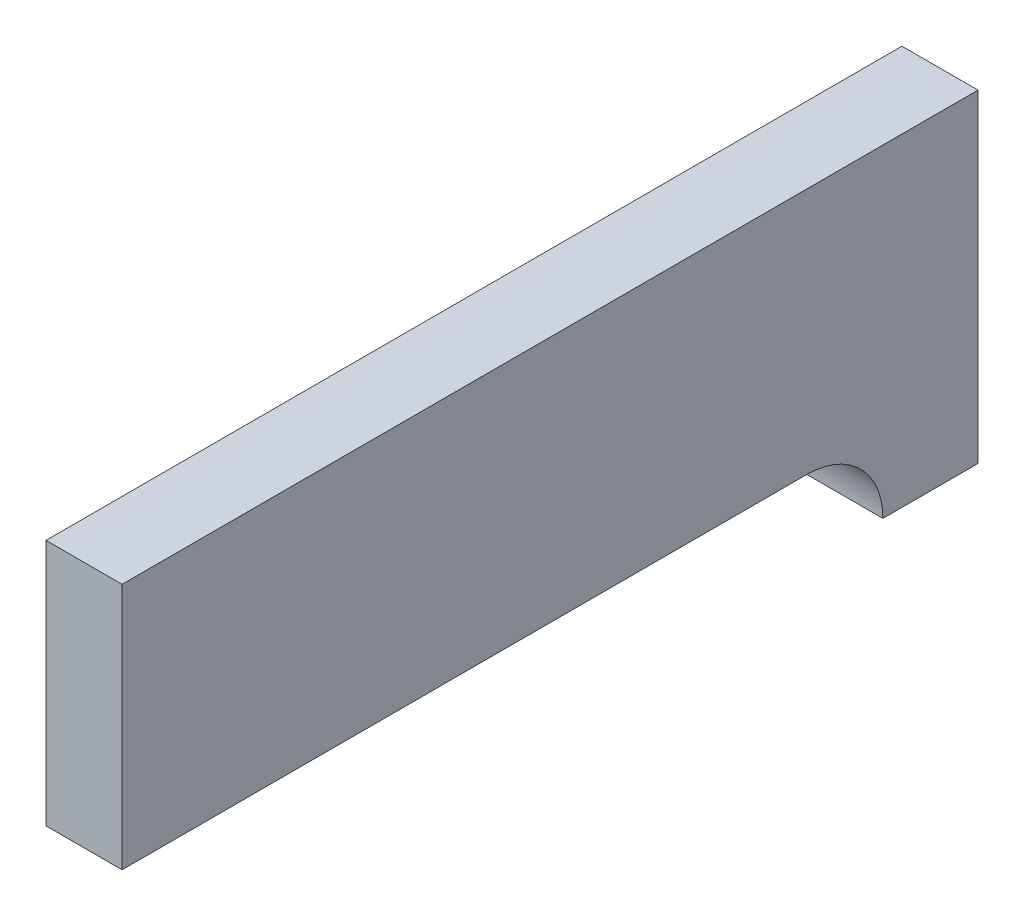
SolidWorks part; units mm, degrees
ref_plane "Front Plane" through (0, 0, 0) normal (0, 0, 1) x (1, 0, 0)
ref_plane "Top Plane" through (0, 0, 0) normal (0, 1, 0) x (1, 0, 0)
ref_plane "Right Plane" through (0, 0, 0) normal (1, 0, 0) x (0, 0, -1)
sketch "Sketch1" plane through (0, 0, 0) normal (0, 0, 1) x (1, 0, 0)
  line L1 (0, 0) -> (48, 0)
  line L2 (0, 0) -> (0, 53)
  line L3 (0, 53) -> (48, 53)
  line L4 (48, 0) -> (48, 53)
  dimension "D1" = 53
  dimension "D2" = 48
extrude "Boss-Extrude1" add sketch "Sketch1" along normal blind 10
sketch "Sketch2" plane through (0, 0, 0) normal (0, 0, -1) x (-1, 0, 0)
  line L0 (0, 53) -> (0, 0) construction
  line L1 (-48, 0) -> (0, 0)
  line L2 (-48, 0) -> (-48, -5.6163)
  line L3 (-48, -5.6163) -> (0, -5.6163)
  line L4 (0, 0) -> (0, -5.6163)
  dimension "D1" = 5.6163
extrude "Boss-Extrude2" add sketch "Sketch2" against normal blind 33.1918
sketch "Sketch4" plane through (0, 0, 10) normal (0, 0, 1) x (1, 0, 0)
  line L1 (0, 53) -> (4, 53)
  line L2 (0, 53) -> (0, 43)
  line L3 (0, 43) -> (4, 43)
  line L4 (4, 53) -> (4, 43)
  line L5 (48, 53) -> (44, 53)
  line L6 (48, 53) -> (48, 43)
  line L7 (48, 43) -> (44, 43)
  line L8 (44, 53) -> (44, 43)
  dimension "D1" = 10
  dimension "D2" = 4
extrude "Boss-Extrude4" add sketch "Sketch4" along normal blind 40
sketch "Sketch5" plane through (0, 0, 10) normal (0, 0, 1) x (1, 0, 0)
  line L0 (48, 0) -> (48, 43) construction
  line L1 (0, 0) -> (48, 0)
  line L2 (0, 0) -> (0, 10.8609)
  line L3 (0, 10.8609) -> (48, 10.8609)
  line L4 (48, 0) -> (48, 10.8609)
  dimension "D1" = 10.8609
extrude "Boss-Extrude5" add sketch "Sketch5" along normal up to surface (23.1918 mm away) up to face at (24, -2.8082, 33.1918)
sketch "Sketch6" plane through (0, -5.6163, 0) normal (0, -1, 0) x (1, 0, 0)
  line L0 (0, 0) -> (0, 28.1918) construction
  line L1 (0, 33.1918) -> (0, 0) construction
  line L2 (48, 33.1918) -> (48, 0) construction
  line L3 (0, 28.1918) -> (48, 28.1918)
  line L4 (0, 28.1918) -> (0, 33.1918)
  line L5 (0, 33.1918) -> (48, 33.1918)
  line L6 (48, 28.1918) -> (48, 33.1918)
  line L8 (48, 33.1918) -> (0, 33.1918) construction
  dimension "D2" = 5
extrude "Boss-Extrude6" add sketch "Sketch6" along normal blind 42.3
sketch "Sketch7" plane through (0, 0, 0) normal (-1, 0, 0) x (0, 0, 1)
  line L0 (33.1918, 10.8609) -> (10, 10.8609) construction
  line L1 (0, -5.6163) -> (-12.8082, -5.6163)
  line L2 (0, -5.6163) -> (0, 10.8609)
  line L3 (0, 10.8609) -> (-12.8082, 10.8609)
  line L4 (-12.8082, -5.6163) -> (-12.8082, 10.8609)
  line L5 (28.1918, -47.9163) -> (28.1918, -5.6163) construction
  dimension "D1" = 41
extrude "Boss-Extrude7" add sketch "Sketch7" against normal up to surface (48 mm away) up to face at (48, 10.6657, 24.2767)
sketch "Sketch8" plane through (0, 0, 28.1918) normal (0, 0, -1) x (-1, 0, 0)
  line L0 (-24, -26.6163) -> (-24, -5.6163) construction
  line L1 (0, -5.6163) -> (-48, -5.6163) construction
  line L3 (-8.5, -42.1163) -> (-39.5, -42.1163) construction
  line L4 (-8.5, -42.1163) -> (-8.5, -11.1163) construction
  line L5 (-8.5, -11.1163) -> (-39.5, -11.1163) construction
  line L6 (-39.5, -42.1163) -> (-39.5, -11.1163) construction
  line L7 (-8.5, -42.1163) -> (-39.5, -11.1163) construction
  line L8 (-8.5, -11.1163) -> (-39.5, -42.1163) construction
  circle A0 centre (-24, -26.6163) radius 11.5
  circle A1 centre (-39.5, -11.1163) radius 2
  circle A2 centre (-39.5, -42.1163) radius 2
  circle A3 centre (-8.5, -11.1163) radius 2
  circle A4 centre (-8.5, -42.1163) radius 2
  dimension "D2" = 23
  dimension "D4" = 4
  dimension "D1" = 21
  dimension "D3" = 31
extrude "Cut-Extrude1" cut sketch "Sketch8" against normal up to next
fillet "Fillet1" radius 10 1 edges at (24, 10.8609, 0)
fillet "Fillet2" radius 4 2 edges at (2, 43, 10) (46, 43, 10)
sketch "Sketch9" plane through (48, 0, 0) normal (1, 0, 0) x (0, 0, -1)
  line L1 (12.8082, 10.8609) -> (17.8082, 10.8609)
  line L2 (12.8082, 10.8609) -> (12.8082, -5.6163)
  line L3 (12.8082, -5.6163) -> (17.8082, -5.6163)
  line L4 (17.8082, 10.8609) -> (17.8082, -5.6163)
  line L5 (-28.1918, -5.6163) -> (12.8082, -5.6163) construction
  dimension "D1" = 5
extrude "Boss-Extrude9" add sketch "Sketch9" against normal up to surface (48 mm away) contours L4 L3 L2 L1 up to face at (0, 13.3569, 15.8852)
sketch "Sketch10" plane through (0, 0, 10) normal (0, 0, 1) x (1, 0, 0)
  line L0 (4, 53) -> (9, 35) construction
  line L1 (9, 35) -> (39, 35) construction
  line L2 (39, 35) -> (44, 53) construction
  line L3 (44, 53) -> (4, 53) construction
  line L4 (44, 53) -> (44, 43) construction
  line L6 (12.429, 36.9797) -> (9, 38.9595)
  line L7 (9, 38.9595) -> (5.571, 36.9797)
  line L8 (5.571, 36.9797) -> (5.571, 33.0203)
  line L9 (5.571, 33.0203) -> (9, 31.0405)
  line L10 (9, 31.0405) -> (12.429, 33.0203)
  line L11 (12.429, 33.0203) -> (12.429, 36.9797)
  line L12 (35.571, 36.9797) -> (35.571, 33.0203)
  line L13 (35.571, 33.0203) -> (39, 31.0405)
  line L14 (39, 31.0405) -> (42.429, 33.0203)
  line L15 (42.429, 33.0203) -> (42.429, 36.9797)
  line L16 (42.429, 36.9797) -> (39, 38.9595)
  line L17 (39, 38.9595) -> (35.571, 36.9797)
  circle A0 centre (9, 35) radius 3.429 construction
  circle A1 centre (39, 35) radius 3.429 construction
  dimension "D1" = 6.858
  dimension "D2" = 30
  dimension "D3" = 18
extrude "Cut-Extrude2" cut sketch "Sketch10" against normal blind 6
sketch "Sketch11" plane through (0, 0, 4) normal (0, 0, 1) x (1, 0, 0)
  circle A0 centre (9, 35) radius 1.9304
  circle A1 centre (39, 35) radius 1.9304
  dimension "D1" = 3.8608
extrude "Cut-Extrude3" cut sketch "Sketch11" against normal blind 6
sketch "Sketch12" plane through (0, 53, 0) normal (0, 1, 0) x (1, 0, 0)
  line L0 (0, 0) -> (0, -50)
  line L1 (0, -50) -> (4, -50)
  line L2 (4, -50) -> (4, -10)
  line L3 (4, -10) -> (44, -10)
  line L4 (44, -10) -> (44, -50)
  line L5 (44, -50) -> (48, -50)
  line L6 (48, -50) -> (48, 0)
  line L7 (48, 0) -> (0, 0)
extrude "Boss-Extrude11" add sketch "Sketch12" along normal blind 3
sketch "Sketch14" plane through (0, 0, 0) normal (-1, 0, 0) x (0, 0, 1)
  line L1 (50, 56) -> (5, 56)
  line L2 (50, 56) -> (50, 39)
  line L3 (50, 39) -> (5, 39)
  line L4 (5, 56) -> (5, 39)
  line L5 (-51.5523, -59.0806) -> (94.7012, -59.0806)
  line L6 (-51.5523, -59.0806) -> (-51.5523, 84.5528)
  line L7 (-51.5523, 84.5528) -> (94.7012, 84.5528)
  line L8 (94.7012, -59.0806) -> (94.7012, 84.5528)
  dimension "D1" = 45
extrude "Cut-Extrude5" cut sketch "Sketch14" against normal through all
sketch "Sketch15" plane through (48, 0, 0) normal (1, 0, 0) x (0, 0, -1)
  line L1 (-66.1579, 62.8642) -> (2.1852, 62.8642)
  line L2 (-66.1579, 62.8642) -> (-66.1579, 24.616)
  line L3 (-66.1579, 24.616) -> (2.1852, 24.616)
  line L4 (2.1852, 62.8642) -> (2.1852, 24.616)
extrude "Cut-Extrude6" cut sketch "Sketch15" against normal up to surface (44 mm away) up to face at (4, 47.5657, 26.6343)
